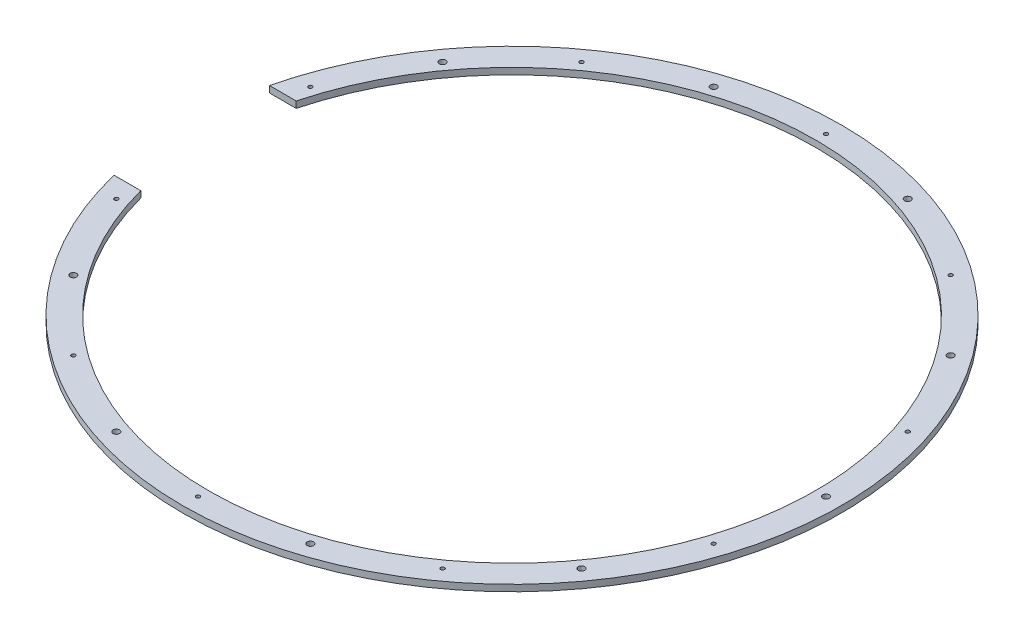
SolidWorks part; units mm, degrees
ref_plane "Front Plane" through (0, 0, 0) normal (0, 0, 1) x (1, 0, 0)
ref_plane "Top Plane" through (0, 0, 0) normal (0, 1, 0) x (1, 0, 0)
ref_plane "Right Plane" through (0, 0, 0) normal (1, 0, 0) x (0, 0, -1)
sketch "Sketch1" plane through (0, 0, 0) normal (0, 1, 0) x (1, 0, 0)
  circle A0 centre (0, 0) radius 254.5
  circle A1 centre (0, 0) radius 234.5
extrude "Boss-Extrude1" add sketch "Sketch1" along normal blind 5
sketch "Sketch2" plane through (0, 5, 0) normal (0, 1, 0) x (1, 0, 0)
  line L0 (-254.5, 0) -> (-226.6942, 0)
  line L1 (-226.6942, 0) -> (-226.6942, 60)
  line L2 (-226.6942, 60) -> (-254.5, 60)
  line L3 (-254.5, 60) -> (-254.5, 0)
  circle A0 centre (0, 0) radius 254.5 construction
  circle A1 centre (0, 0) radius 234.5 construction
  dimension "D1" = 60
extrude "Cut-Extrude1" cut sketch "Sketch2" against normal blind 5
mirror "Mirror1" about plane through (0, 0, 0) normal (0, 0, 1) of "Cut-Extrude1"
sketch "Sketch3" plane through (0, 5, 0) normal (0, 1, 0) x (1, 0, 0)
  circle A0 centre (242.5, 0) radius 2.5
  circle A1 centre (196.1866, -142.5379) radius 2.5
  circle A2 centre (74.9366, -230.6312) radius 2.5
  circle A3 centre (-74.9366, -230.6312) radius 2.5
  circle A4 centre (-196.1866, -142.5379) radius 2.5
  circle A5 centre (-242.5, 0) radius 2.5
  circle A6 centre (-196.1866, 142.5379) radius 2.5
  circle A7 centre (-74.9366, 230.6312) radius 2.5
  circle A8 centre (74.9366, 230.6312) radius 2.5
  circle A9 centre (196.1866, 142.5379) radius 2.5
  point P23 (0, 0)
  dimension "D1" = 242.5
  dimension "D2" = 10
extrude "Cut-Extrude2" cut sketch "Sketch3" against normal blind 5
sketch "Sketch4" plane through (0, 5, 0) normal (0, 1, 0) x (1, 0, 0)
  arc A0 (196.1866, 142.5379) -> (242.5, 0) centre (0, 0) cw
  circle A1 centre (230.6312, 74.9366) radius 1.5
  circle A2 centre (230.6312, -74.9366) radius 1.5
  circle A3 centre (142.5379, -196.1866) radius 1.5
  circle A4 centre (0, -242.5) radius 1.5
  circle A5 centre (-142.5379, -196.1866) radius 1.5
  circle A6 centre (-230.6312, -74.9366) radius 1.5
  circle A7 centre (-230.6312, 74.9366) radius 1.5
  circle A8 centre (-142.5379, 196.1866) radius 1.5
  circle A9 centre (0, 242.5) radius 1.5
  circle A10 centre (142.5379, 196.1866) radius 1.5
  circle A11 centre (230.6312, -74.9366) radius 1.5
  circle A12 centre (142.5379, -196.1866) radius 1.5
  circle A13 centre (0, -242.5) radius 1.5
  circle A14 centre (-142.5379, -196.1866) radius 1.5
  circle A15 centre (-230.6312, -74.9366) radius 1.5
  circle A16 centre (-230.6312, 74.9366) radius 1.5
  circle A17 centre (-142.5379, 196.1866) radius 1.5
  circle A18 centre (0, 242.5) radius 1.5
  circle A19 centre (142.5379, 196.1866) radius 1.5
  point P28 (0, 0)
  point P47 (0, 0)
  dimension "D1" = 10
  dimension "D2" = 10
extrude "Cut-Extrude3" cut sketch "Sketch4" against normal blind 5 contours A4 | A5 | A6 | A7 | A8 | A9 | A10 | A1 | A2 | A3
